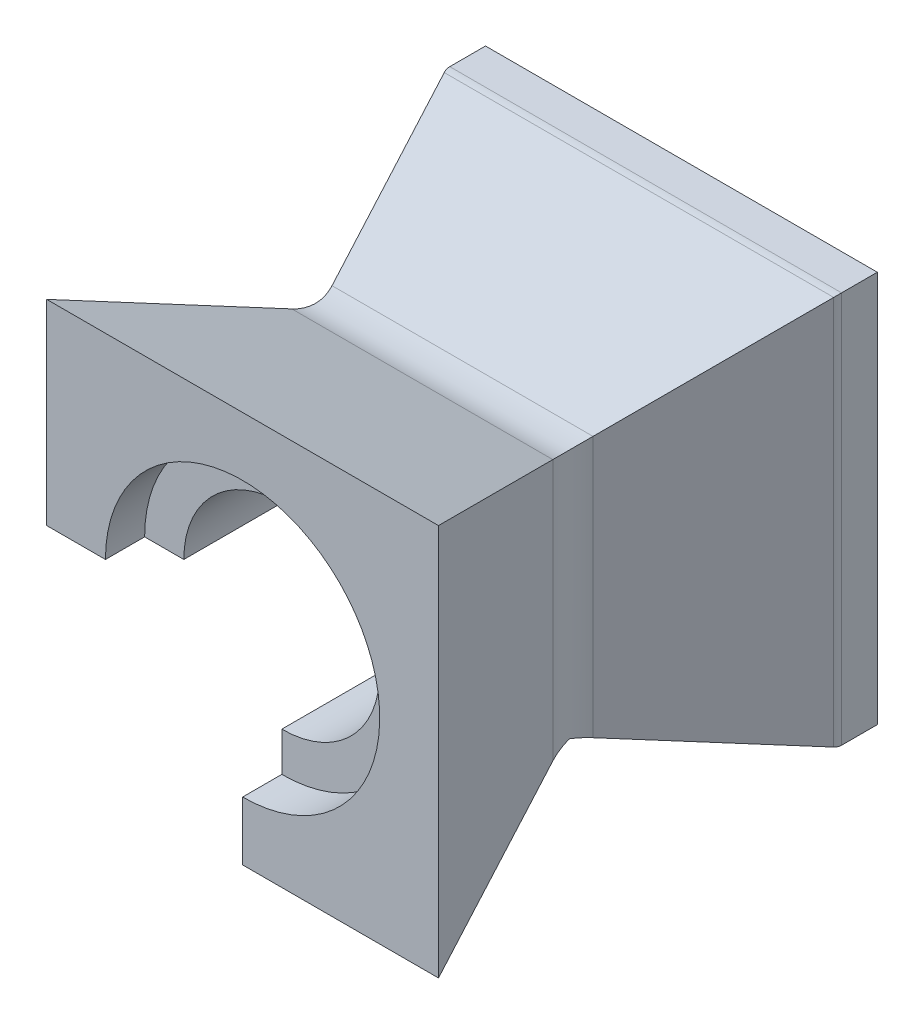
SolidWorks part; units mm, degrees
material "Acier inoxydable moulé"
ref_plane "Plan de face" through (0, 0, 0) normal (0, 0, 1) x (1, 0, 0)
ref_plane "Plan de dessus" through (0, 0, 0) normal (0, 1, 0) x (1, 0, 0)
ref_plane "Plan de droite" through (0, 0, 0) normal (1, 0, 0) x (0, 0, -1)
sketch "Esquisse2" plane through (0, 0, 0) normal (0, 0, 1) x (1, 0, 0)
  line L1 (-73.4104, 39.1618) -> (26.5896, 39.1618)
  line L2 (-73.4104, 39.1618) -> (-73.4104, -60.8382)
  line L3 (-73.4104, -60.8382) -> (26.5896, -60.8382)
  line L4 (26.5896, 39.1618) -> (26.5896, -60.8382)
  dimension "D1" = 100
  dimension "D2" = 100
extrude "Boss.-Extru.1" add sketch "Esquisse2" along normal blind 51 draft 20
mirror "Symétrie4" about plane through (0, 0, 51) normal (0, 0, 1) of "Boss.-Extru.1"
sketch "Esquisse3" plane through (0, 0, 102) normal (0, 0, 1) x (1, 0, 0)
  line L0 (26.5896, 39.1618) -> (-73.4104, -60.8382) construction
  line L1 (-73.4104, 39.1618) -> (26.5896, -60.8382) construction
  circle A0 centre (-23.4104, -10.8382) radius 25
  point P10 (-23.4104, -10.8382)
  point P11 (-23.4104, -10.8382)
  point P12 (-23.4104, -10.8382)
  dimension "D1" = 50
extrude "Enlèv. mat.-Extru.1" cut sketch "Esquisse3" against normal through all both and the other way through all
sketch "Esquisse5" plane through (0, 0, 102) normal (0, 0, 1) x (1, 0, 0)
  circle A0 centre (-23.4104, -10.8382) radius 35
  dimension "D1" = 70
extrude "Enlèv. mat.-Extru.2" cut sketch "Esquisse5" against normal blind 10 and the other way through all
sketch "Esquisse6" plane through (0, 0, 0) normal (0, 0, -1) x (-1, 0, 0)
  circle A1 centre (23.4104, -10.8382) radius 35
  circle A2 centre (23.4104, -10.8382) radius 35
  dimension "D1" = 0
extrude "Enlèv. mat.-Extru.3" cut sketch "Esquisse6" against normal blind 10
sketch "Esquisse7" plane through (0, 0, 0) normal (0, 0, -1) x (-1, 0, 0)
  line L0 (23.4104, -10.8382) -> (73.4104, -10.8382)
  line L1 (73.4104, 39.1618) -> (73.4104, -60.8382) construction
  line L2 (23.4104, -10.8382) -> (23.4104, -60.8382)
  line L3 (73.4104, -60.8382) -> (-26.5896, -60.8382) construction
  line L4 (23.4104, -60.8382) -> (73.4104, -60.8382)
  line L5 (73.4104, -60.8382) -> (73.4104, -10.8382)
extrude "Enlèv. mat.-Extru.4" cut sketch "Esquisse7" against normal through all
fillet "Congé1" radius 15 3 edges at (-54.8479, 4.8806, 51) (-23.4104, 20.5994, 51) (8.0271, -10.8382, 51)
sketch "Esquisse8" plane through (0, 0, 0) normal (0, 0, -1) x (-1, 0, 0)
  line L0 (23.4104, -10.8382) -> (-11.9449, 24.5172) construction
  line L1 (-26.5896, 39.1618) -> (-26.5896, -60.8382)
  line L2 (-11.9449, -46.1935) -> (58.7657, 24.5172) construction
  line L3 (-17.2482, 29.8205) -> (-6.6416, 19.2139) construction
  line L4 (-15.1269, 31.9418) -> (-4.5203, 21.3352)
  line L5 (-19.3696, 27.6992) -> (-8.763, 17.0926)
  line L6 (-4.5203, 17.0926) -> (-26.5896, 39.1618) construction
  line L7 (-17.2482, -51.4968) -> (-6.6416, -40.8902) construction
  line L12 (-19.3696, -49.3755) -> (-8.763, -38.7689)
  line L13 (-15.1269, -53.6181) -> (-4.5203, -43.0115)
  line L14 (53.4624, 19.2139) -> (64.069, 29.8205) construction
  line L15 (51.3411, 21.3352) -> (61.9477, 31.9418)
  line L16 (55.5838, 17.0926) -> (66.1904, 27.6992)
  line L17 (73.4104, -10.8382) -> (58.4104, -10.8382) construction
  line L18 (73.4104, 39.1618) -> (73.4104, -10.8382) construction
  line L19 (-26.5896, 39.1618) -> (73.4104, 39.1618) construction
  line L20 (-23.5896, 36.1618) -> (-23.5896, -57.8382)
  line L21 (23.4104, -60.8382) -> (-26.5896, -60.8382) construction
  line L22 (23.4104, -45.8382) -> (23.4104, -60.8382) construction
  line L23 (23.4104, -57.8382) -> (23.4104, -60.8382)
  line L24 (23.4104, -60.8382) -> (-26.5896, -60.8382)
  line L25 (-26.5896, 39.1618) -> (73.4104, 39.1618)
  line L26 (73.4104, 39.1618) -> (73.4104, -10.8382)
  line L27 (73.4104, -10.8382) -> (70.4104, -10.8382)
  line L29 (-26.5896, 36.1618) -> (73.4104, 36.1618)
  line L30 (-23.5896, 36.1618) -> (70.4104, 36.1618)
  line L32 (70.4104, 39.1618) -> (70.4104, -10.8382)
  line L33 (70.4104, 36.1618) -> (70.4104, -10.8382)
  line L35 (23.4104, -57.8382) -> (-26.5896, -57.8382)
  line L36 (23.4104, -57.8382) -> (-23.5896, -57.8382)
  circle A0 centre (23.4104, -10.8382) radius 50 construction
  arc A1 (-15.1269, 31.9418) -> (-19.3696, 27.6992) centre (-17.2482, 29.8205) ccw
  arc A2 (-8.763, 17.0926) -> (-4.5203, 21.3352) centre (-6.6416, 19.2139) ccw
  arc A7 (-19.3696, -49.3755) -> (-15.1269, -53.6181) centre (-17.2482, -51.4968) ccw
  arc A8 (-4.5203, -43.0115) -> (-8.763, -38.7689) centre (-6.6416, -40.8902) ccw
  arc A9 (51.3411, 21.3352) -> (55.5838, 17.0926) centre (53.4624, 19.2139) ccw
  arc A10 (66.1904, 27.6992) -> (61.9477, 31.9418) centre (64.069, 29.8205) ccw
  point P11 (-11.9449, 24.5172)
  point P18 (-11.9449, -46.1935)
  point P28 (58.7657, 24.5172)
  point P40 (-23.5896, 39.1618)
  point P41 (-23.5896, -60.8382)
  dimension "D1" = 15
  dimension "D2" = 3
  dimension "D3" = 3
  dimension "D4" = 15
  dimension "D5" = 15
  dimension "D6" = 3
  dimension "D7" = 3
  dimension "D8" = 3
extrude "Enlèv. mat.-Extru.8" cut sketch "Esquisse8" against normal blind 10 contours L5 A2 L4 A1 | L13 A8 L12 A7 | L15 A10 L16 A9
sketch "Esquisse9" plane through (0, 0, 0) normal (0, 0, -1) x (-1, 0, 0)
  line L2 (-4.5203, 21.3352) -> (-15.1269, 31.9418)
  line L3 (-19.3696, 27.6992) -> (-8.763, 17.0926)
  line L4 (-4.5203, 21.3352) -> (-15.1269, 31.9418)
  line L5 (-19.3696, 27.6992) -> (-8.763, 17.0926)
  line L6 (-8.763, -38.7689) -> (-19.3696, -49.3755)
  line L7 (-15.1269, -53.6181) -> (-4.5203, -43.0115)
  line L8 (-8.763, -38.7689) -> (-19.3696, -49.3755)
  line L9 (-15.1269, -53.6181) -> (-4.5203, -43.0115)
  line L10 (61.9477, 31.9418) -> (51.3411, 21.3352)
  line L11 (55.5838, 17.0926) -> (66.1904, 27.6992)
  line L12 (61.9477, 31.9418) -> (51.3411, 21.3352)
  line L13 (55.5838, 17.0926) -> (66.1904, 27.6992)
  line L22 (-26.5896, -60.8382) -> (23.4104, -60.8382)
  line L23 (-26.5896, 39.1618) -> (-26.5896, -60.8382)
  line L24 (73.4104, 39.1618) -> (-26.5896, 39.1618)
  line L25 (73.4104, -10.8382) -> (73.4104, 39.1618)
  line L26 (70.4104, -10.8382) -> (73.4104, -10.8382)
  line L27 (70.4104, 36.1618) -> (70.4104, -10.8382)
  line L28 (-23.5896, 36.1618) -> (70.4104, 36.1618)
  line L29 (-23.5896, -57.8382) -> (-23.5896, 36.1618)
  line L30 (23.4104, -57.8382) -> (-23.5896, -57.8382)
  line L31 (23.4104, -60.8382) -> (23.4104, -57.8382)
  line L32 (-26.5896, -60.8382) -> (23.4104, -60.8382)
  line L33 (-26.5896, 39.1618) -> (-26.5896, -60.8382)
  line L34 (73.4104, 39.1618) -> (-26.5896, 39.1618)
  line L35 (73.4104, -10.8382) -> (73.4104, 39.1618)
  line L36 (70.4104, -10.8382) -> (73.4104, -10.8382)
  line L37 (70.4104, 36.1618) -> (70.4104, -10.8382)
  line L38 (-23.5896, 36.1618) -> (70.4104, 36.1618)
  line L39 (-23.5896, -57.8382) -> (-23.5896, 36.1618)
  line L40 (23.4104, -57.8382) -> (-23.5896, -57.8382)
  line L41 (23.4104, -60.8382) -> (23.4104, -57.8382)
  arc A2 (-8.763, 17.0926) -> (-4.5203, 21.3352) centre (-6.6416, 19.2139) ccw
  arc A3 (-15.1269, 31.9418) -> (-19.3696, 27.6992) centre (-17.2482, 29.8205) ccw
  arc A4 (-8.763, 17.0926) -> (-4.5203, 21.3352) centre (-6.6416, 19.2139) ccw
  arc A5 (-15.1269, 31.9418) -> (-19.3696, 27.6992) centre (-17.2482, 29.8205) ccw
  arc A6 (-4.5203, -43.0115) -> (-8.763, -38.7689) centre (-6.6416, -40.8902) ccw
  arc A7 (-19.3696, -49.3755) -> (-15.1269, -53.6181) centre (-17.2482, -51.4968) ccw
  arc A8 (-4.5203, -43.0115) -> (-8.763, -38.7689) centre (-6.6416, -40.8902) ccw
  arc A9 (-19.3696, -49.3755) -> (-15.1269, -53.6181) centre (-17.2482, -51.4968) ccw
  arc A10 (66.1904, 27.6992) -> (61.9477, 31.9418) centre (64.069, 29.8205) ccw
  arc A11 (51.3411, 21.3352) -> (55.5838, 17.0926) centre (53.4624, 19.2139) ccw
  arc A12 (66.1904, 27.6992) -> (61.9477, 31.9418) centre (64.069, 29.8205) ccw
  arc A13 (51.3411, 21.3352) -> (55.5838, 17.0926) centre (53.4624, 19.2139) ccw
  dimension "D1" = 0
  dimension "D2" = 0
  dimension "D3" = 0
  dimension "D4" = 0
extrude "Boss.-Extru.2" add sketch "Esquisse9" along normal blind 10 contours L32 L41 L40 L39 L38 L37 L36 L35 L34 L33
fillet "Congé2" radius 5 4 edges at (-73.4104, 14.1618, 0) (-23.4104, 39.1618, 0) (26.5896, -10.8382, 0) (1.5896, -60.8382, 0)
equation "\"A\"= 102"
equation "\"B\"= 100"
equation "\"C\"= 20"
equation "\"D1@Esquisse2\"=\"B\""
equation "\"D2@Esquisse2\"=\"B\""
equation "\"D3@Boss.-Extru.1\"=\"C\""
equation "\"D1@Boss.-Extru.1\"=\"A\"/2"
